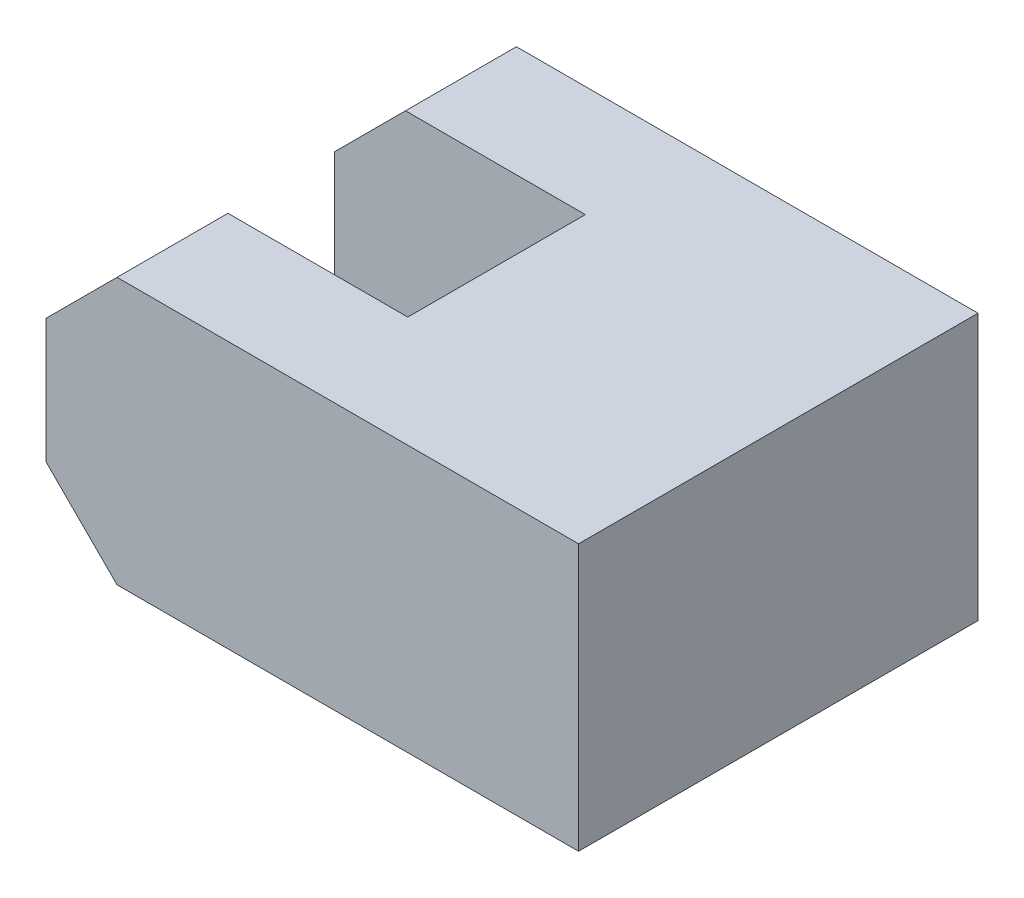
SolidWorks part; units mm, degrees
ref_plane "Спереди" through (0, 0, 0) normal (0, 0, 1) x (1, 0, 0)
ref_plane "Сверху" through (0, 0, 0) normal (0, 1, 0) x (1, 0, 0)
ref_plane "Справа" through (0, 0, 0) normal (1, 0, 0) x (0, 0, -1)
sketch "Эскиз1" plane through (0, 0, 0) normal (0, 1, 0) x (1, 0, 0)
  line L0 (-8.5273, 0) -> (45.8432, 0)
  line L1 (-49.0191, 22.5) -> (10.9809, 22.5)
  line L2 (-49.0191, 22.5) -> (-49.0191, -22.5)
  line L3 (-49.0191, -22.5) -> (10.9809, -22.5)
  line L4 (10.9809, 22.5) -> (10.9809, -22.5)
extrude "Вытянуть1" add sketch "Эскиз1" along normal blind 30
sketch "Эскиз3" plane through (0, 30, 0) normal (0, 1, 0) x (1, 0, 0)
  line L0 (-38.6818, 0) -> (-47.6939, 0) construction
  line L3 (-56.6305, 10) -> (-20.7593, 10)
  line L4 (-56.6305, 10) -> (-56.6305, -10)
  line L5 (-56.6305, -10) -> (-20.7593, -10)
  line L6 (-20.7593, 10) -> (-20.7593, -10)
  line L7 (-56.6305, 10) -> (-20.7593, -10) construction
  line L8 (-56.6305, -10) -> (-20.7593, 10) construction
  point P1 (-38.6949, 0)
extrude "Вытянуть3" cut sketch "Эскиз3" against normal through all
chamfer "Фаска1" distance 8 angle 45 4 edges at (-49.0191, 0, -16.25) (-49.0191, 30, -16.25) (-49.0191, 0, 16.25) (-49.0191, 30, 16.25)
